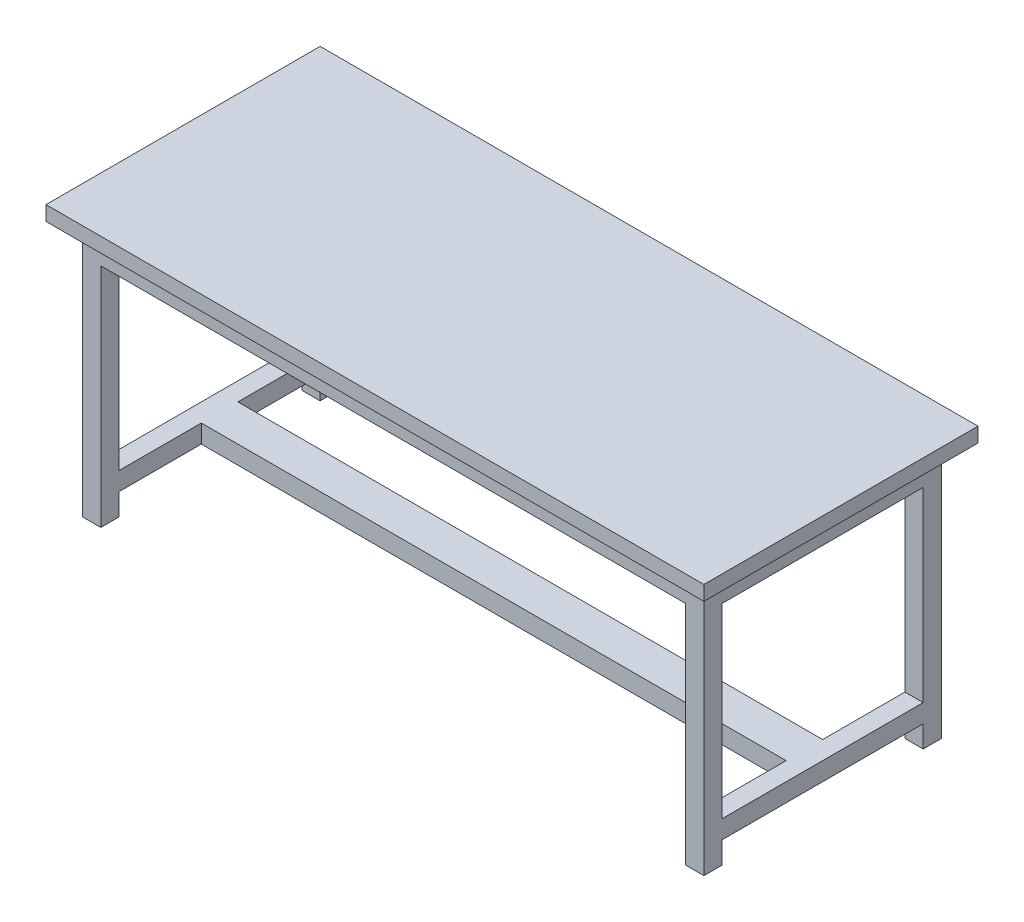
SolidWorks part; units mm, degrees
ref_plane "正面" through (0, 0, 0) normal (0, 0, 1) x (1, 0, 0)
ref_plane "平面" through (0, 0, 0) normal (0, 1, 0) x (1, 0, 0)
ref_plane "右側面" through (0, 0, 0) normal (1, 0, 0) x (0, 0, -1)
sketch "ｽｹｯﾁ1" plane through (0, 0, 0) normal (0, 1, 0) x (1, 0, 0)
  line L1 (0, 0) -> (1800, 0)
  line L2 (0, 0) -> (0, 750)
  line L3 (0, 750) -> (1800, 750)
  line L4 (1800, 0) -> (1800, 750)
  dimension "D1" = 1800
  dimension "D2" = 750
extrude "ﾎﾞｽ - 押し出し1" add sketch "ｽｹｯﾁ1" along normal blind 40
sketch "ｽｹｯﾁ2" plane through (0, 0, 0) normal (0, -1, 0) x (-1, 0, 0)
  line L0 (-1800, 750) -> (0, 750) construction
  line L1 (-1750, 50) -> (-1700, 50)
  line L2 (-1750, 50) -> (-1750, 100)
  line L3 (-1750, 100) -> (-1700, 100)
  line L4 (-1700, 50) -> (-1700, 100)
  line L5 (-1750, 650) -> (-1700, 650)
  line L6 (-1750, 650) -> (-1750, 700)
  line L7 (-1750, 700) -> (-1700, 700)
  line L8 (-1700, 650) -> (-1700, 700)
  line L9 (-100, 50) -> (-50, 50)
  line L10 (-100, 50) -> (-100, 100)
  line L11 (-100, 100) -> (-50, 100)
  line L12 (-50, 50) -> (-50, 100)
  line L13 (-100, 650) -> (-50, 650)
  line L14 (-100, 650) -> (-100, 700)
  line L15 (-100, 700) -> (-50, 700)
  line L16 (-50, 650) -> (-50, 700)
  line L17 (0, 0) -> (-1800, 0) construction
  line L18 (0, 750) -> (0, 0) construction
  line L19 (-1800, 0) -> (-1800, 750) construction
  dimension "D1" = 50
  dimension "D2" = 50
  dimension "D3" = 50
  dimension "D4" = 50
  dimension "D5" = 50
  dimension "D6" = 50
  dimension "D7" = 50
  dimension "D8" = 50
  dimension "D9" = 50
  dimension "50" = 50
  dimension "D10" = 50
  dimension "D11" = 50
  dimension "D12" = 50
  dimension "D13" = 50
  dimension "D14" = 50
  dimension "D15" = 50
extrude "ﾎﾞｽ - 押し出し2" add sketch "ｽｹｯﾁ2" along normal blind 700
sketch "ｽｹｯﾁ3" plane through (0, 0, 0) normal (0, -1, 0) x (-1, 0, 0)
  line L1 (-1750, 650) -> (-1700, 650)
  line L2 (-1750, 650) -> (-1750, 100)
  line L3 (-1750, 100) -> (-1700, 100)
  line L4 (-1700, 650) -> (-1700, 100)
  line L5 (-1700, 50) -> (-100, 50)
  line L6 (-1700, 50) -> (-1700, 100)
  line L7 (-1700, 100) -> (-100, 100)
  line L8 (-100, 50) -> (-100, 100)
  line L9 (-50, 100) -> (-100, 100)
  line L10 (-50, 100) -> (-50, 650)
  line L11 (-50, 650) -> (-100, 650)
  line L12 (-100, 100) -> (-100, 650)
  line L13 (-100, 700) -> (-1700, 700)
  line L14 (-100, 700) -> (-100, 650)
  line L15 (-100, 650) -> (-1700, 650)
  line L16 (-1700, 700) -> (-1700, 650)
  line M2 (-100, 50) -> (-100, 100)
  line M3 (-100, 100) -> (-50, 100)
  line M7 (-1750, 100) -> (-1700, 100)
  line M8 (-1700, 100) -> (-1700, 50)
  line M13 (-1700, 650) -> (-1750, 650)
  line M16 (-1700, 700) -> (-1700, 650)
  line M17 (-50, 650) -> (-100, 650)
  line M18 (-100, 650) -> (-100, 700)
extrude "ﾎﾞｽ - 押し出し3" add sketch "ｽｹｯﾁ3" along normal blind 80 contours L4 L2 M13 M7 | L15 L13 M18 M16 | L7 L5 M8 M2 | L12 L10 M3 M17
sketch "ｽｹｯﾁ4" plane through (0, 0, -650) normal (0, 0, 1) x (1, 0, 0)
  line L0 (1750, -700) -> (1750, -80) construction
  line L1 (1750, -640) -> (1700, -640)
  line L2 (1750, -640) -> (1750, -590)
  line L3 (1750, -590) -> (1700, -590)
  line L4 (1700, -640) -> (1700, -590)
  line L5 (1700, -700) -> (1700, -80) construction
  line L6 (100, -700) -> (100, -80) construction
  line L7 (100, -640) -> (50, -640)
  line L8 (100, -640) -> (100, -590)
  line L9 (100, -590) -> (50, -590)
  line L10 (50, -640) -> (50, -590)
  line L11 (50, -700) -> (50, -80) construction
  line L12 (1750, -700) -> (1700, -700) construction
  line L13 (100, -700) -> (50, -700) construction
  dimension "D1" = 50
  dimension "D2" = 50
  dimension "D3" = 60
  dimension "D4" = 60
extrude "ﾎﾞｽ - 押し出し4" add sketch "ｽｹｯﾁ4" along normal up to next
sketch "ｽｹｯﾁ5" plane through (1700, 0, 0) normal (-1, 0, 0) x (0, 0, 1)
  line L0 (-100, -590) -> (-650, -590) construction
  line L1 (-325, -590) -> (-425, -590)
  line L2 (-325, -590) -> (-325, -640)
  line L3 (-325, -640) -> (-425, -640)
  line L4 (-425, -590) -> (-425, -640)
  line L5 (-100, -640) -> (-650, -640) construction
  line L6 (-50, -700) -> (-50, -80) construction
  dimension "D1" = 100
  dimension "D2" = 275
extrude "ﾎﾞｽ - 押し出し5" add sketch "ｽｹｯﾁ5" along normal up to next
